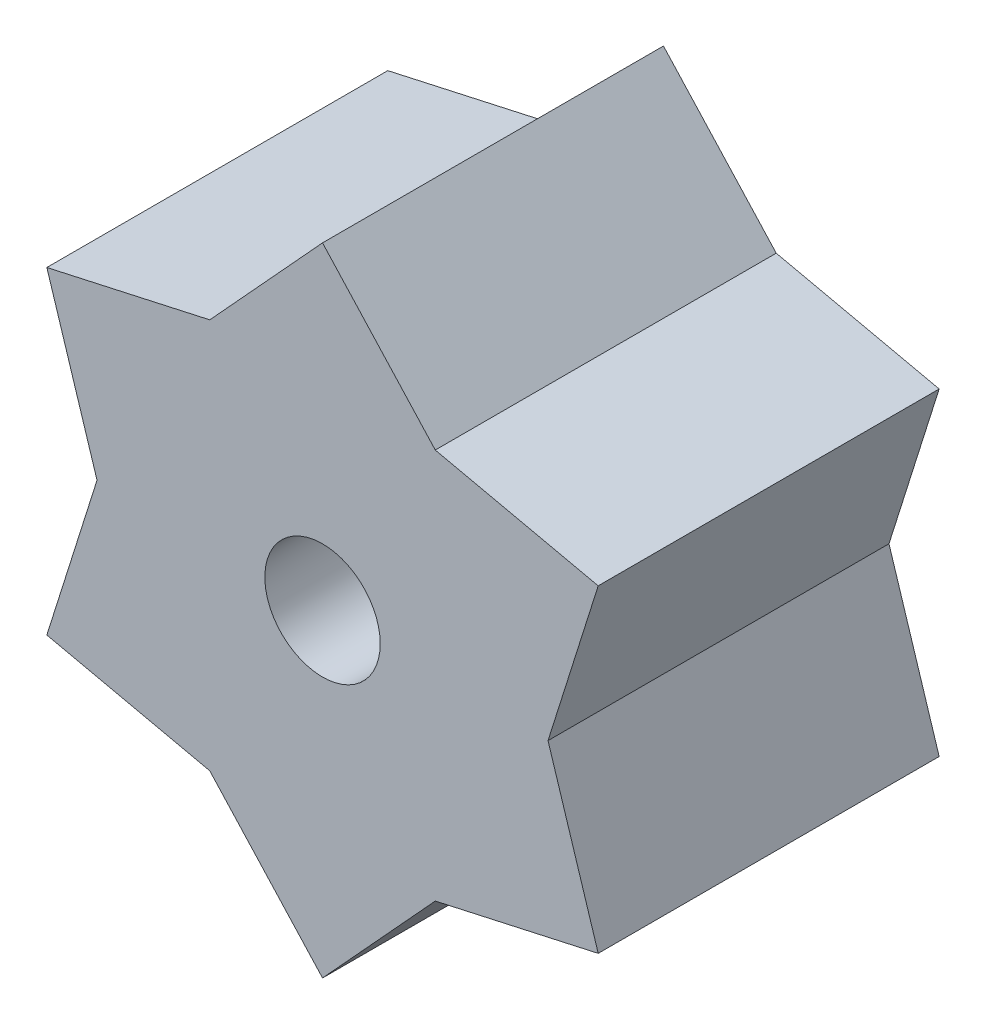
SolidWorks part; units mm, degrees
ref_plane "Front Plane" through (0, 0, 0) normal (0, 0, 1) x (1, 0, 0)
ref_plane "Top Plane" through (0, 0, 0) normal (0, 1, 0) x (1, 0, 0)
ref_plane "Right Plane" through (0, 0, 0) normal (1, 0, 0) x (0, 0, -1)
sketch "Sketch1" plane through (0, 0, 0) normal (0, 0, 1) x (1, 0, 0)
  line L0 (0, 6.0688) -> (0, -5.749) construction
  line L1 (-3.0228, 2.7699) -> (0, 6.0688)
  line L2 (0, 6.0688) -> (3.0228, 2.7699)
  line L3 (0.8874, 4.0028) -> (5.2557, 3.0344)
  line L4 (5.2557, 3.0344) -> (3.9102, -1.2329)
  line L5 (3.9102, 1.2329) -> (5.2557, -3.0344)
  line L6 (5.2557, -3.0344) -> (0.8874, -4.0028)
  line L7 (3.0228, -2.7699) -> (0, -6.0688)
  line L8 (0, -6.0688) -> (-3.0228, -2.7699)
  line L9 (-0.8874, -4.0028) -> (-5.2557, -3.0344)
  line L10 (-5.2557, -3.0344) -> (-3.9102, 1.2329)
  line L11 (-3.9102, -1.2329) -> (-5.2557, 3.0344)
  line L12 (-5.2557, 3.0344) -> (-0.8874, 4.0028)
  circle A0 centre (0, 0) radius 1.1
  circle A1 centre (0, 0) radius 4.1
  point P26 (0, 0)
  dimension "D1" = 2.2
  dimension "D3" = 85
  dimension "D4" = 42.5
  dimension "D2" = 3
  dimension "D5" = 6
extrude "Boss-Extrude1" add sketch "Sketch1" against normal blind 6.5
